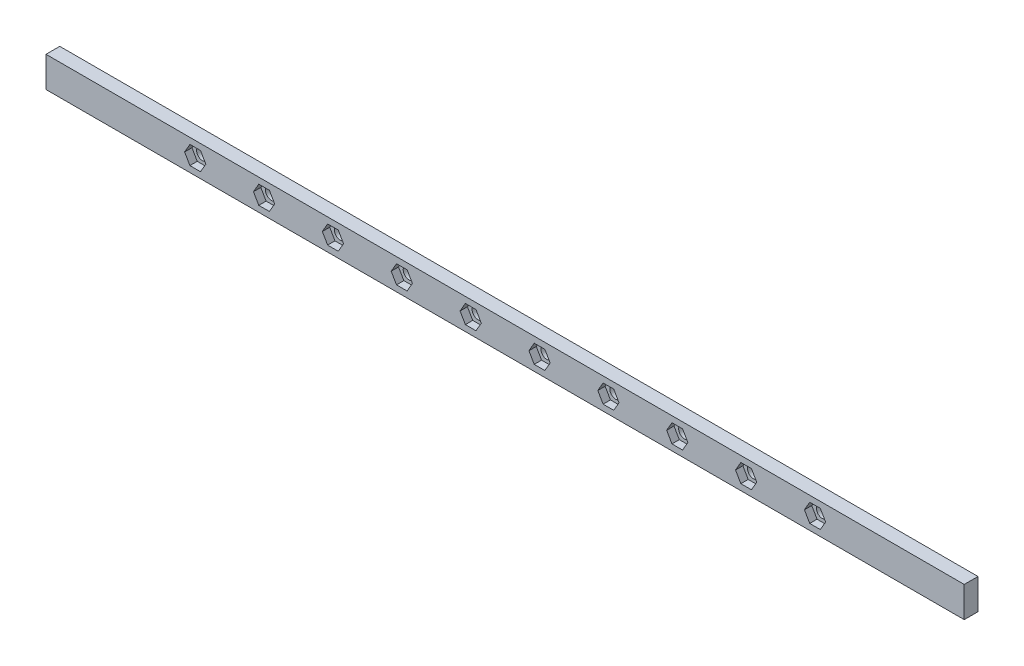
SolidWorks part; units mm, degrees
material "Epoxy, sin carga"
ref_plane "Alzado" through (0, 0, 0) normal (0, 0, 1) x (1, 0, 0)
ref_plane "Planta" through (0, 0, 0) normal (0, 1, 0) x (1, 0, 0)
ref_plane "Vista lateral" through (0, 0, 0) normal (1, 0, 0) x (0, 0, -1)
sketch "Sketch2" plane through (0, 0, 0) normal (0, 0, 1) x (1, 0, 0)
  line L1 (-100, -3.325) -> (100, -3.325)
  line L2 (-100, -3.325) -> (-100, 3.325)
  line L3 (-100, 3.325) -> (100, 3.325)
  line L4 (100, -3.325) -> (100, 3.325)
  line L5 (-100, -3.325) -> (100, 3.325) construction
  line L6 (-100, 3.325) -> (100, -3.325) construction
  point P0 (0, 0)
  dimension "D1" = 200
  dimension "D2" = 6.65
extrude "Boss-Extrude1" add sketch "Sketch2" along normal blind 3
sketch "Sketch3" plane through (0, 0, 3) normal (0, 0, 1) x (1, 0, 0)
  line L0 (0, 0) -> (-7.5, 0) construction
  line L1 (-5.1906, 0) -> (-6.3453, 2)
  line L2 (-6.3453, 2) -> (-8.6547, 2)
  line L3 (-8.6547, 2) -> (-9.8094, 0)
  line L4 (-9.8094, 0) -> (-8.6547, -2)
  line L5 (-8.6547, -2) -> (-6.3453, -2)
  line L6 (-6.3453, -2) -> (-5.1906, 0)
  line L7 (0, -1000) -> (0, 49000) construction
  line L8 (5.1906, 0) -> (6.3453, 2)
  line L9 (6.3453, 2) -> (8.6547, 2)
  line L10 (8.6547, 2) -> (9.8094, 0)
  line L11 (9.8094, 0) -> (8.6547, -2)
  line L12 (8.6547, -2) -> (6.3453, -2)
  line L13 (6.3453, -2) -> (5.1906, 0)
  circle A0 centre (-7.5, 0) radius 2 construction
  circle A1 centre (7.5, 0) radius 2 construction
  dimension "D1" = 4
  dimension "D2" = 15
extrude "Cut-Extrude1" cut sketch "Sketch3" against normal blind 1.6
pattern_linear "LPattern1" count 5 spacing 15 along (-1, 0, 0) count 5 spacing 15 along (1, 0, 0) of "Cut-Extrude1"
sketch "Sketch6" plane through (0, 0, 3) normal (0, 0, 1) x (1, 0, 0)
  point P0 (37.5, 0)
  point P2 (52.5, 0)
  point P4 (67.5, 0)
  point P6 (22.5, 0)
  point P8 (7.5, 0)
  point P10 (-67.5, 0)
  point P12 (-52.5, 0)
  point P14 (-37.5, 0)
  point P16 (-7.5, 0)
  point P18 (-22.5, 0)
hole_wizard "Taladro de margen para M21" positions "Sketch6" profile "Sketch7" hole size "M2" standard "ISO"
sketch "Sketch7" plane through (37.5, 0, 3) normal (1, 0, 0) x (0, -1, 0)
  line L0 (0, 0) -> (0, 13.2811)
  line L1 (0, 13.2811) -> (1.3, 12.5)
  line L2 (1.3, 12.5) -> (1.3, 0)
  line L5 (1.3, 0) -> (0, 0)
  line L10 (0, 13.2811) -> (-1.3, 12.5) construction
  line L11 (0, -6.35) -> (0, 107.95) construction
  dimension "Diámetro de taladro" = 2.6
  dimension "Profundidad de taladro" = 12.5
  dimension "Ángulo de perforador" = 118
